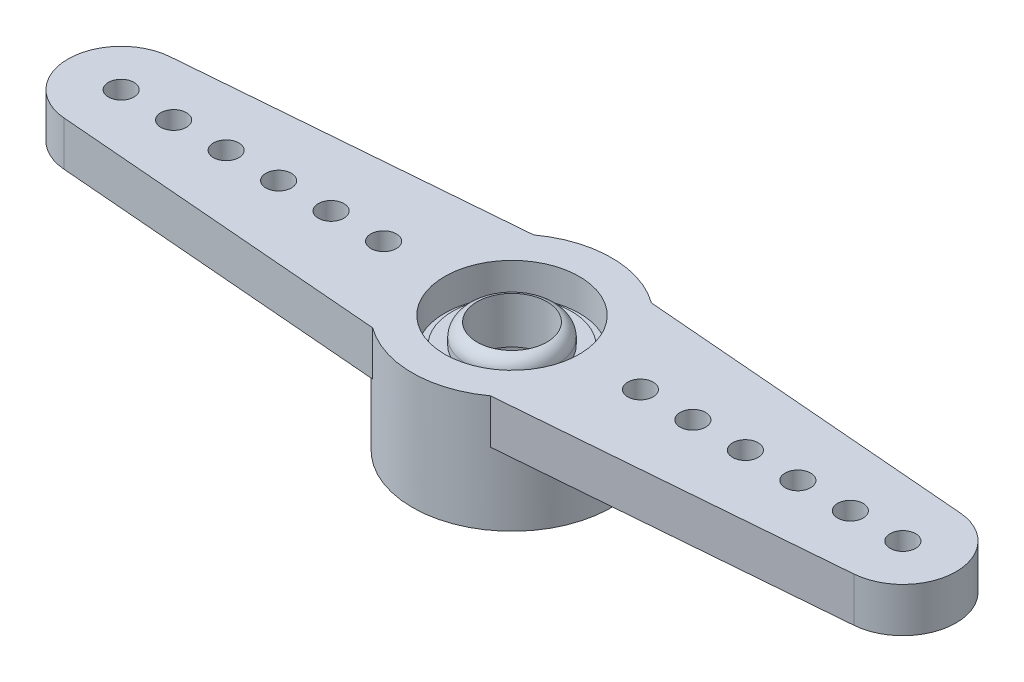
SolidWorks part; units mm, degrees
material "Nylon 101"
ref_plane "Front Plane" through (0, 0, 0) normal (0, 0, 1) x (1, 0, 0)
ref_plane "Top Plane" through (0, 0, 0) normal (0, 1, 0) x (1, 0, 0)
ref_plane "Right Plane" through (0, 0, 0) normal (1, 0, 0) x (0, 0, -1)
sketch "Sketch18" plane through (0, 0, 0) normal (0, 1, 0) x (1, 0, 0)
  line L0 (14.1859, 0) -> (-14.1859, 0) construction
  line L1 (-14.3431, 1.924) -> (-2.1374, 2.921)
  line L2 (-14.3431, -1.924) -> (-2.1374, -2.921)
  line L3 (14.3431, -1.924) -> (2.1374, -2.921)
  line L4 (14.3431, 1.924) -> (2.1374, 2.921)
  arc A0 (-2.1374, -2.921) -> (2.1374, -2.921) centre (0, 0) ccw
  arc A1 (-14.3431, 1.924) -> (-14.3431, -1.924) centre (-14.1859, 0) ccw
  arc A2 (14.3431, -1.924) -> (14.3431, 1.924) centre (14.1859, 0) ccw
  arc A3 (2.1374, 2.921) -> (-2.1374, 2.921) centre (0, 0) ccw
  point P3 (0, 0)
  dimension "D1" = 1.9304
  dimension "D2" = 3.6195
  dimension "D3" = 28.3718
  dimension "D5" = 5.842
  dimension "D8" = 1.9304
  dimension "D4" = 2.921
extrude "Extrude17" add sketch "Sketch18" along normal blind 1.6129
sketch "Sketch19" plane through (0, 1.6129, 0) normal (0, 1, 0) x (1, 0, 0)
  circle A0 centre (0, 0) radius 3.6195
  arc A1 (-2.1374, -2.921) -> (2.1374, -2.921) centre (0, 0) ccw construction
extrude "Extrude19" add sketch "Sketch19" against normal blind 4.2291
sketch "Sketch20" plane through (0, 1.6129, 0) normal (0, 1, 0) x (1, 0, 0)
  line L0 (-14.1859, 0) -> (-12.2809, 0) construction
  line L1 (-12.2809, 0) -> (-10.3759, 0) construction
  line L2 (-10.3759, 0) -> (-8.4709, 0) construction
  line L3 (-8.4709, 0) -> (-6.5659, 0) construction
  line L4 (-6.5659, 0) -> (-4.6609, 0) construction
  line L5 (-4.6609, 0) -> (-2.7559, 0) construction
  line L6 (-2.7559, 0) -> (0, 0) construction
  circle A0 centre (-14.1859, 0) radius 0.4636
  circle A1 centre (0, 0) radius 1.27
  circle A3 centre (-4.6609, 0) radius 0.4636
  circle A4 centre (-6.5659, 0) radius 0.4636
  circle A5 centre (-8.4709, 0) radius 0.4636
  circle A6 centre (-10.3759, 0) radius 0.4636
  circle A7 centre (-12.2809, 0) radius 0.4636
  dimension "D1" = 0.9271
  dimension "D3" = 2.54
  dimension "D2" = 1.905
extrude "Extrude20" cut sketch "Sketch20" against normal through all
sketch "Sketch21" plane through (0, 1.6129, 0) normal (0, 1, 0) x (1, 0, 0)
  circle A0 centre (0, 0) radius 2.4447
  dimension "D1" = 4.8895
extrude "Extrude21" cut sketch "Sketch21" against normal blind 1.1557
sketch "Sketch22" plane through (0, -2.6162, 0) normal (0, -1, 0) x (1, 0, 0)
  circle A0 centre (0, 0) radius 2.286
  dimension "D1" = 4.572
extrude "Extrude22" cut sketch "Sketch22" against normal blind 2.3368
sketch "Sketch23" plane through (0, 0.4572, 0) normal (0, 1, 0) x (1, 0, 0)
  circle A0 centre (0, 0) radius 2.159
  dimension "D1" = 4.318
extrude "Extrude23" add sketch "Sketch23" along normal blind 0.2032 separate body
sketch "Sketch24" plane through (0, 0.6604, 0) normal (0, 1, 0) x (1, 0, 0)
  circle A0 centre (0, 0) radius 1.651
  dimension "D1" = 3.302
extrude "Extrude24" add sketch "Sketch24" along normal blind 0.762
sketch "Sketch25" plane through (0, 1.4224, 0) normal (0, 1, 0) x (1, 0, 0)
  line L0 (0, -1.651) -> (0, 1.651) construction
  line L1 (-1.651, 0) -> (1.651, 0) construction
  line L2 (0.254, -1.016) -> (-0.254, -1.016)
  line L3 (-0.254, -1.016) -> (-0.254, -0.254)
  line L4 (-0.254, -0.254) -> (-1.016, -0.254)
  line L5 (-1.016, -0.254) -> (-1.016, 0.254)
  line L6 (0.254, 1.016) -> (-0.254, 1.016)
  line L7 (-0.254, 1.016) -> (-0.254, 0.254)
  line L8 (-0.254, 0.254) -> (-1.016, 0.254)
  line L9 (0.254, 1.016) -> (0.254, 0.254)
  line L10 (0.254, -1.016) -> (0.254, -0.254)
  line L11 (0.254, -0.254) -> (1.016, -0.254)
  line L12 (1.016, -0.254) -> (1.016, 0.254)
  line L13 (0.254, 0.254) -> (1.016, 0.254)
  circle A0 centre (0, 0) radius 1.651 construction
  point P16 (-1.016, 0)
  point P17 (0, 1.016)
  point P19 (0, -1.016)
  dimension "D1" = 2.032
  dimension "D2" = 0.508
extrude "Extrude25" cut sketch "Sketch25" against normal blind 0.508
fillet "Fillet1" radius 0.508 1 edges at (0, 1.4224, 1.651)
mirror "Mirror1" about plane through (0, 0, 0) normal (1, 0, 0) of "Extrude20"
